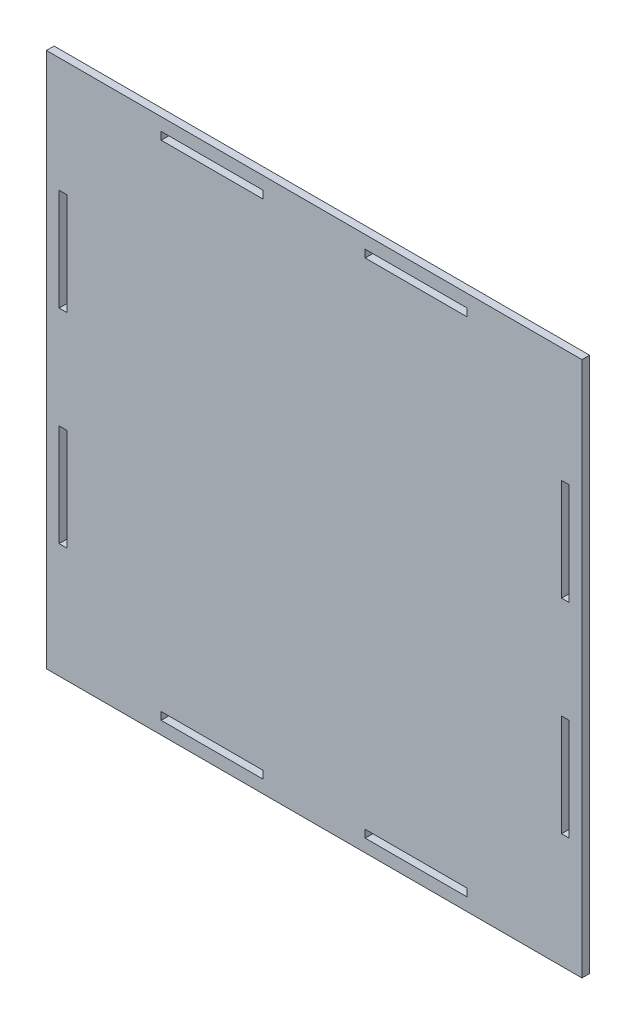
SolidWorks part; units mm, degrees
ref_plane "前视基准面" through (0, 0, 0) normal (0, 0, 1) x (1, 0, 0)
ref_plane "上视基准面" through (0, 0, 0) normal (0, 1, 0) x (1, 0, 0)
ref_plane "右视基准面" through (0, 0, 0) normal (1, 0, 0) x (0, 0, -1)
sketch "草图1" plane through (0, 0, 0) normal (0, 0, 1) x (1, 0, 0)
  line L0 (0, -100) -> (200, -100)
  line L1 (0, 0) -> (200, 0)
  line L2 (0, 0) -> (0, -200)
  line L3 (0, -200) -> (200, -200)
  line L4 (200, 0) -> (200, -200)
  line L5 (100, 0) -> (100, -200)
  line L6 (200, -80) -> (197, -80)
  line L7 (40, 0) -> (80, 0)
  line L8 (40, 0) -> (40, -3)
  line L9 (40, -3) -> (80, -3)
  line L10 (80, 0) -> (80, -3)
  line L11 (0, -40) -> (3, -40)
  line L12 (0, -40) -> (0, -80)
  line L13 (0, -80) -> (3, -80)
  line L14 (3, -40) -> (3, -80)
  line L15 (197, -40) -> (197, -80)
  line L16 (200, -40) -> (197, -40)
  line L17 (200, -40) -> (200, -80)
  line L18 (160, -3) -> (120, -3)
  line L19 (120, 0) -> (120, -3)
  line L20 (160, 0) -> (120, 0)
  line L21 (160, 0) -> (160, -3)
  line L22 (200, -160) -> (200, -120)
  line L23 (200, -160) -> (197, -160)
  line L24 (197, -160) -> (197, -120)
  line L25 (200, -120) -> (197, -120)
  line L26 (160, -200) -> (160, -197)
  line L27 (160, -200) -> (120, -200)
  line L28 (120, -200) -> (120, -197)
  line L29 (160, -197) -> (120, -197)
  line L30 (40, -197) -> (80, -197)
  line L31 (80, -200) -> (80, -197)
  line L32 (40, -200) -> (80, -200)
  line L33 (40, -200) -> (40, -197)
  line L34 (0, -120) -> (3, -120)
  line L35 (3, -160) -> (3, -120)
  line L36 (0, -160) -> (3, -160)
  line L37 (0, -160) -> (0, -120)
  line L39 (0, 0) -> (200, 0)
  line L40 (0, 0) -> (0, 5)
  line L41 (0, 5) -> (200, 5)
  line L42 (200, 0) -> (200, 5)
  line L43 (200, 5) -> (205, 5)
  line L44 (200, 5) -> (200, -200)
  line L45 (200, -200) -> (205, -200)
  line L46 (205, 5) -> (205, -200)
  line L47 (205, -200) -> (0, -200)
  line L48 (205, -200) -> (205, -205)
  line L49 (205, -205) -> (0, -205)
  line L50 (0, -200) -> (0, -205)
  line L51 (0, -205) -> (-5, -205)
  line L52 (0, -205) -> (0, 5)
  line L53 (0, 5) -> (-5, 5)
  line L54 (-5, -205) -> (-5, 5)
  dimension "D1" = 200
  dimension "D2" = 200
  dimension "D3" = 3
  dimension "D4" = 40
  dimension "D5" = 40
  dimension "D6" = 3
  dimension "D7" = 40
  dimension "D8" = 40
  dimension "D9" = 5
  dimension "D10" = 5
  dimension "D11" = 5
  dimension "D12" = 5
extrude "凸台-拉伸1" add sketch "草图1" along normal blind 3 contours L11 L14 L13 L2 L0 L5 L1 L10 L9 L8 | L36 L2 L3 L33 L30 L31 L5 L0 L34 L35 | L1 L21 L18 L19 L5 L0 L4 L6 L15 L16 | L29 L26 L3 L4 L23 L24 L25 L0 L5 L28 | L54 L51 L50 L2 L40 L53 | L1 L42 L41 L40 | L46 L43 L42 L4 L45 | L3 L50 L49 L48 L45
